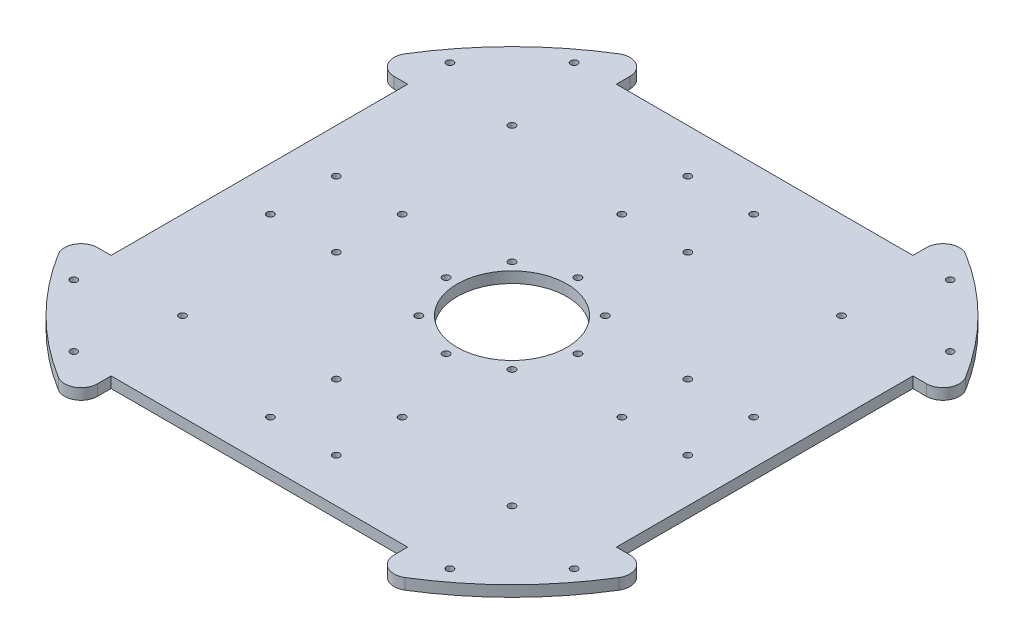
SolidWorks part; units mm, degrees
ref_plane "Front Plane" through (0, 0, 0) normal (0, 0, 1) x (1, 0, 0)
ref_plane "Top Plane" through (0, 0, 0) normal (0, 1, 0) x (1, 0, 0)
ref_plane "Right Plane" through (0, 0, 0) normal (1, 0, 0) x (0, 0, -1)
sketch "Sketch1" plane through (0, 0, 0) normal (0, 1, 0) x (1, 0, 0)
  line L0 (160, 67.5) -> (115, 67.5)
  line L5 (-67.5, 160) -> (67.5, 160)
  line L6 (-67.5, 160) -> (-67.5, 115)
  line L7 (-67.5, 115) -> (67.5, 115)
  line L8 (67.5, 160) -> (67.5, 115)
  line L9 (160, 67.5) -> (160, -67.5)
  line L10 (160, -67.5) -> (115, -67.5)
  line L11 (115, 67.5) -> (115, -67.5)
  line L12 (67.5, -160) -> (67.5, -115)
  line L13 (67.5, -160) -> (-67.5, -160)
  line L14 (-67.5, -160) -> (-67.5, -115)
  line L15 (67.5, -115) -> (-67.5, -115)
  line L16 (-160, -67.5) -> (-115, -67.5)
  line L17 (-160, -67.5) -> (-160, 67.5)
  line L18 (-160, 67.5) -> (-115, 67.5)
  line L19 (-115, -67.5) -> (-115, 67.5)
  line L20 (0, 150) -> (0, 115) construction
  line L21 (0, 160) -> (0, 150) construction
  circle A0 centre (0, 0) radius 150
  point P7 (0, 115)
  point P23 (0, 0)
  dimension "D1" = 300
  dimension "D4" = 35
  dimension "D2" = 135
  dimension "D5" = 10
  dimension "D3" = 4
extrude "Boss-Extrude1" add sketch "Sketch1" along normal blind 5 contours L12 A0 L10 L11 L0 L8 L7 L6 L18 L19 L16 L14 L15
fillet "Fillet1" radius 7.5 8 edges at (-133.9543, 2.5, 67.5) (-133.9543, 2.5, -67.5) (-67.5, 2.5, -133.9543) (67.5, 2.5, -133.9543) (133.9543, 2.5, -67.5) (133.9543, 2.5, 67.5) (67.5, 2.5, 133.9543) (-67.5, 2.5, 133.9543)
sketch "Sketch3" plane through (0, 5, 0) normal (0, 1, 0) x (1, 0, 0)
  line L0 (0, -115) -> (0, -80) construction
  line L1 (67.5, -115) -> (-67.5, -115) construction
  line L2 (-15, -95) -> (15, -95) construction
  line L3 (-115, 0) -> (-80, 0) construction
  line L4 (-95, 15) -> (-95, -15) construction
  line L5 (0, 115) -> (0, 80) construction
  line L6 (15, 95) -> (-15, 95) construction
  line L7 (115, 0) -> (80, 0) construction
  line L8 (95, -15) -> (95, 15) construction
  line L9 (-115, -67.5) -> (-115, 67.5) construction
  circle A0 centre (-15, -95) radius 1.6
  circle A1 centre (-15, -65) radius 1.6
  circle A2 centre (15, -65) radius 1.6
  circle A3 centre (15, -95) radius 1.6
  circle A4 centre (-65, 15) radius 1.6
  circle A5 centre (-65, -15) radius 1.6
  circle A6 centre (-95, -15) radius 1.6
  circle A7 centre (-95, 15) radius 1.6
  circle A8 centre (15, 65) radius 1.6
  circle A9 centre (-15, 65) radius 1.6
  circle A10 centre (-15, 95) radius 1.6
  circle A11 centre (15, 95) radius 1.6
  circle A12 centre (65, -15) radius 1.6
  circle A13 centre (65, 15) radius 1.6
  circle A14 centre (95, 15) radius 1.6
  circle A15 centre (95, -15) radius 1.6
  point P7 (0, -95)
  point P16 (0, -80)
  point P48 (0, 0)
  dimension "D1" = 3.2
  dimension "D2" = 30
  dimension "D3" = 35
  dimension "D4" = 4
  dimension "D5" = 4
extrude "Cut-Extrude2" cut sketch "Sketch3" against normal through all both and the other way through all
sketch "Sketch4" plane through (0, 5, 0) normal (0, 1, 0) x (1, 0, 0)
  circle A0 centre (0, 0) radius 25
  circle A1 centre (0, 30) radius 1.6
  circle A2 centre (21.2132, 21.2132) radius 1.6
  circle A3 centre (30, 0) radius 1.6
  circle A4 centre (21.2132, -21.2132) radius 1.6
  circle A5 centre (0, -30) radius 1.6
  circle A6 centre (-21.2132, -21.2132) radius 1.6
  circle A7 centre (-30, 0) radius 1.6
  circle A8 centre (-21.2132, 21.2132) radius 1.6
  point P22 (0, 0)
  dimension "D1" = 50
  dimension "D2" = 3.2
  dimension "D3" = 30
  dimension "D4" = 8
extrude "Cut-Extrude3" cut sketch "Sketch4" against normal through all both and the other way through all
sketch "Sketch5" plane through (0, 5, 0) normal (0, 1, 0) x (1, 0, 0)
  line L0 (75, -75) -> (106.066, -106.066) construction
  line L1 (-75, -75) -> (-106.066, -106.066) construction
  line L2 (-115, 0) -> (115, 0) construction
  line L3 (-115, -67.5) -> (-115, 67.5) construction
  line L4 (115, 67.5) -> (115, -67.5) construction
  circle A0 centre (75, -75) radius 1.6
  circle A1 centre (-75, -75) radius 1.6
  arc A2 (78.9474, -127.5434) -> (127.5434, -78.9474) centre (0, 0) ccw construction
  arc A3 (-127.5434, -78.9474) -> (-78.9474, -127.5434) centre (0, 0) ccw construction
  circle A9 centre (75, 75) radius 1.6
  circle A10 centre (-75, 75) radius 1.6
  dimension "D1" = 3.2
  dimension "D2" = 150
extrude "Cut-Extrude4" cut sketch "Sketch5" against normal through all both and the other way through all
sketch "Sketch6" plane through (0, 5, 0) normal (0, 1, 0) x (1, 0, 0)
  line L0 (0, 0) -> (-106.066, -106.066) construction
  line L1 (0, 0) -> (-106.066, 106.066) construction
  line L3 (-75, 75) -> (-88.3393, 61.6607) construction
  line L5 (-75, -75) -> (-65.1472, -84.8528) construction
  arc A0 (-127.5434, -78.9474) -> (-78.9474, -127.5434) centre (0, 0) ccw construction
  circle A1 centre (-113.8909, -85.6066) radius 1.6
  circle A3 centre (-85.6066, -113.8909) radius 1.6
  arc A11 (-78.9474, 127.5434) -> (-127.5434, 78.9474) centre (0, 0) ccw construction
  circle A18 centre (-113.8909, 85.6066) radius 1.6
  circle A19 centre (-85.6066, 113.8909) radius 1.6
  circle A20 centre (85.6066, 113.8909) radius 1.6
  circle A21 centre (113.8909, 85.6066) radius 1.6
  circle A22 centre (113.8909, -85.6066) radius 1.6
  circle A23 centre (85.6066, -113.8909) radius 1.6
  point P25 (0, 0)
  point P31 (0, -0.7538)
  point P33 (0, 0)
  dimension "D1" = 3.2
  dimension "D2" = 40
  dimension "D3" = 35
  dimension "D5" = 35
  dimension "D4" = 4
extrude "Cut-Extrude5" cut sketch "Sketch6" against normal through all both and the other way through all
